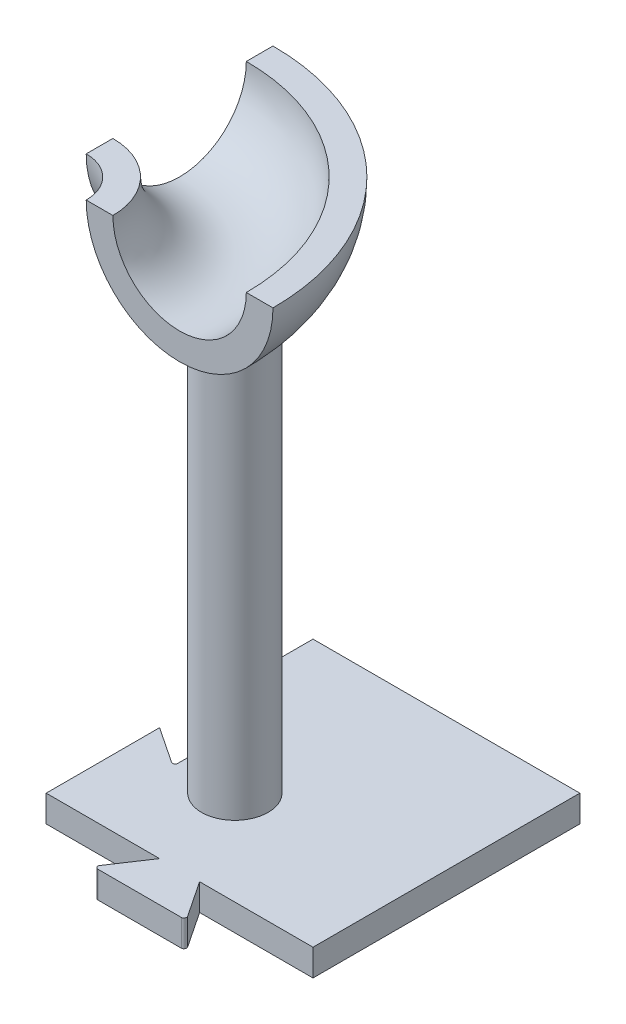
SolidWorks part; units mm, degrees
ref_plane "Front Plane" through (0, 0, 0) normal (0, 0, 1) x (1, 0, 0)
ref_plane "Top Plane" through (0, 0, 0) normal (0, 1, 0) x (1, 0, 0)
ref_plane "Right Plane" through (0, 0, 0) normal (1, 0, 0) x (0, 0, -1)
sketch "Sketch1" plane through (0, 0, 0) normal (0, 1, 0) x (1, 0, 0)
  line L1 (-50, -50) -> (50, -50)
  line L2 (-50, -50) -> (-50, 50)
  line L3 (-50, 50) -> (50, 50)
  line L4 (50, -50) -> (50, 50)
  line L5 (-50, -50) -> (50, 50) construction
  line L6 (-50, 50) -> (50, -50) construction
  point P0 (0, 0)
  dimension "D1" = 100
extrude "Boss-Extrude1" add sketch "Sketch1" along normal blind 10
ref_plane "Plane1" through (0, 210, 0) normal (0, 1, 0) x (1, 0, 0)
sketch "Sketch2" plane through (0, 210, 0) normal (0, 1, 0) x (1, 0, 0)
  line L0 (-50, -50) -> (50, -50) construction
  line L1 (-50, 50) -> (-50, -50) construction
  arc A0 (0, -50) -> (-50, 0) centre (-50, -50) ccw
sketch "Sketch3" plane through (0, 0, 50) normal (0, 0, 1) x (1, 0, 0)
  line L0 (0, 210) -> (-50, 210) construction
  line L1 (25, 210) -> (-25, 210) construction
  line L2 (25, 210) -> (35, 210)
  line L3 (-25, 210) -> (-35, 210)
  line L4 (55, 210) -> (-55, 210) construction
  arc A0 (25, 210) -> (-25, 210) centre (0, 210) cw
  arc A1 (35, 210) -> (-35, 210) centre (0, 210) cw
  arc A2 (25, 210) -> (-25, 210) centre (0, 210) cw construction
  dimension "D1" = 25
  dimension "D2" = 10
sweep "Sweep1" add profiles "Sketch3" path "Sketch2"
sketch "Sketch4" plane through (0, 10, 0) normal (0, 1, 0) x (1, 0, 0)
  circle A0 centre (-14.6447, -14.6447) radius 12.5
  arc A2 (0, -50) -> (-50, 0) centre (-50, -50) ccw construction
  dimension "D1" = 25
extrude "Boss-Extrude2" add sketch "Sketch4" along normal up to next
sketch "Sketch21" plane through (14.2336, 10, 36.5005) normal (0, 1, 0) x (1, 0, 0)
  line L0 (-21.7336, -13.4995) -> (-31.7336, -28.4995)
  line L1 (-64.2336, -13.4995) -> (35.7664, -13.4995) construction
  line L2 (-31.7336, -28.4995) -> (3.2664, -28.4995)
  line L3 (3.2664, -28.4995) -> (-6.7336, -13.4995)
  line L4 (-14.2336, -28.4995) -> (-14.2336, -13.4995) construction
  line L5 (-21.7336, -13.4995) -> (-6.7336, -13.4995)
  line L6 (-14.2336, -28.4995) -> (-14.2336, -13.4995) construction
  dimension "D1" = 15
  dimension "D2" = 35
  dimension "D3" = 15
  dimension "D4" = 0
extrude "Boss-Extrude21" add sketch "Sketch21" against normal up to surface (10 mm away) contours L0 L2 L3 L5 up to face at (0, 0, 0)
fillet "Fillet1" radius 1 2 edges at (-17.5, 5, 65) (17.5, 5, 65)
other "Male-Knob<1>"
sketch "Sketch22" plane through (-40.0286, 10, 2.6049) normal (0, 1, 0) x (1, 0, 0)
  line L0 (-9.9714, -4.8951) -> (5.0286, -14.8951)
  line L1 (-9.9714, 52.6049) -> (-9.9714, -47.3951) construction
  line L2 (5.0286, -14.8951) -> (5.0286, 20.1049)
  line L3 (5.0286, 20.1049) -> (-9.9714, 10.1049)
  line L4 (-9.9714, 10.1049) -> (-9.9714, -4.8951)
  line L5 (5.0286, 2.6049) -> (0, 2.6049) construction
  line L6 (-9.9714, 2.6049) -> (5.0286, 2.6049) construction
  dimension "D1" = 15
  dimension "D2" = 35
  dimension "D3" = 15
  dimension "D4" = 0
extrude "Cut-Extrude1" cut sketch "Sketch22" against normal up to next
fillet "Fillet11" radius 1 2 edges at (-35, 5, -17.5) (-35, 5, 17.5)
other "Female-Slot<1>"
mirror "Mirror1" [suppressed] about plane through (0, 0, 0) normal (1, 0, 0)
delete or keep bodies "Body-Delete/Keep 1" [suppressed] type delete bodies bodies 105
equation "\"height\"= 4"
equation "\"D1@Plane1\"=\"height\"*50"
